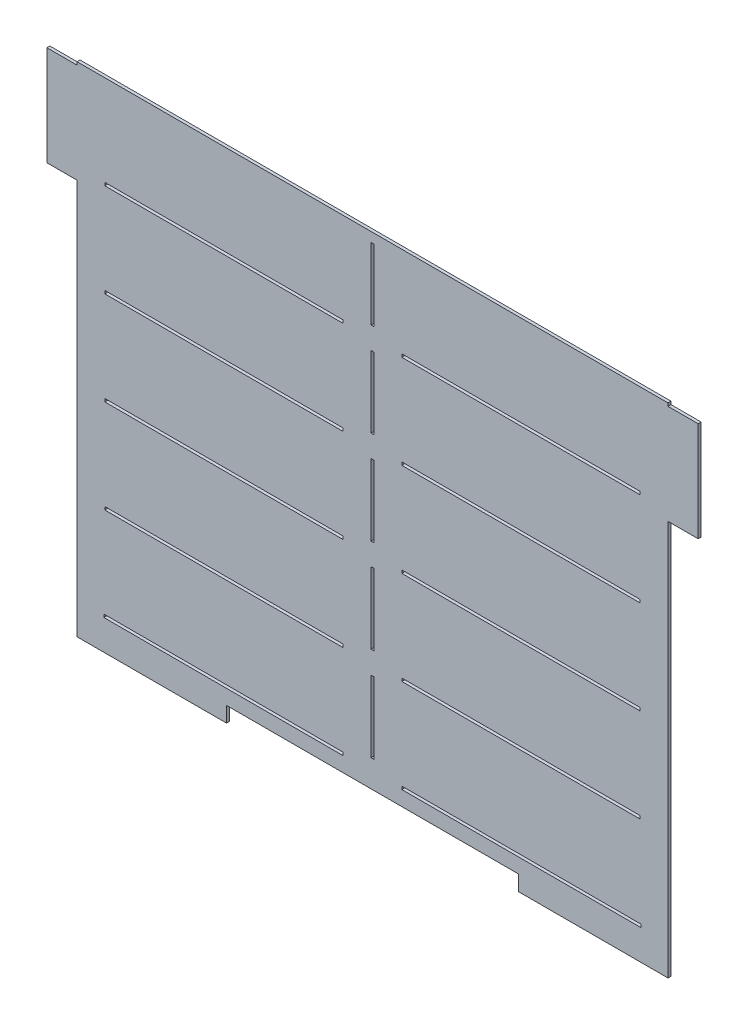
SolidWorks part; units mm, degrees
material "6061-T6 (SS)"
ref_plane "X-Y Datum" through (0, 0, 0) normal (0, 0, 1) x (1, 0, 0)
ref_plane "X-Z Datum" through (0, 0, 0) normal (0, 1, 0) x (1, 0, 0)
ref_plane "Y-Z Datum" through (0, 0, 0) normal (1, 0, 0) x (0, 0, -1)
sketch "Sketch1" plane through (0, 0, 0) normal (0, 0, 1) x (1, 0, 0)
  line L0 (-1.27, -1.27) -> (-1.27, 95.3084)
  line L1 (0, 0) -> (310.8274, 0)
  line L2 (0, 0) -> (0, 94.0384)
  line L3 (0, 94.0384) -> (310.8274, 94.0384)
  line L4 (310.8274, 0) -> (310.8274, 94.0384)
  line L5 (-1.27, 95.3084) -> (312.0974, 95.3084)
  line L6 (312.0974, -1.27) -> (312.0974, 95.3084)
  line L7 (-1.27, -1.27) -> (312.0974, -1.27)
  line L8 (-2.8575, 96.8959) -> (313.6849, 96.8959)
  line L9 (313.6849, -2.8575) -> (313.6849, 96.8959)
  line L10 (-2.8575, -2.8575) -> (313.6849, -2.8575)
  line L11 (-2.8575, -2.8575) -> (-2.8575, 96.8959)
  line L12 (0, 99.7534) -> (310.8274, 99.7534)
  line L13 (310.8274, 193.7918) -> (310.8274, 99.7534)
  line L14 (0, 193.7918) -> (310.8274, 193.7918)
  line L15 (0, 193.7918) -> (0, 99.7534)
  line L16 (-1.27, 195.0618) -> (312.0974, 195.0618)
  line L17 (312.0974, 195.0618) -> (312.0974, 98.4834)
  line L18 (-1.27, 98.4834) -> (312.0974, 98.4834)
  line L19 (-1.27, 195.0618) -> (-1.27, 98.4834)
  line L20 (-2.8575, 196.6493) -> (-2.8575, 96.8959)
  line L21 (-2.8575, 196.6493) -> (630.2273, 196.6493)
  line L23 (-2.8575, 296.4028) -> (630.2273, 296.4028)
  line L24 (-1.27, 198.2368) -> (-1.27, 294.8153)
  line L25 (-1.27, 294.8153) -> (312.0974, 294.8153)
  line L26 (312.0974, 198.2368) -> (312.0974, 294.8153)
  line L27 (-1.27, 198.2368) -> (312.0974, 198.2368)
  line L28 (0, 199.5068) -> (0, 293.5453)
  line L29 (0, 199.5068) -> (310.8274, 199.5068)
  line L30 (310.8274, 199.5068) -> (310.8274, 293.5453)
  line L31 (0, 293.5453) -> (310.8274, 293.5453)
  line L33 (313.6849, 96.8959) -> (313.6849, 196.6493)
  line L34 (-2.8575, 396.1562) -> (630.2273, 396.1562)
  line L35 (-1.27, 394.5687) -> (312.0974, 394.5687)
  line L36 (312.0974, 394.5687) -> (312.0974, 297.9903)
  line L37 (-1.27, 297.9903) -> (312.0974, 297.9903)
  line L38 (-1.27, 394.5687) -> (-1.27, 297.9903)
  line L39 (0, 393.2987) -> (310.8274, 393.2987)
  line L40 (310.8274, 393.2987) -> (310.8274, 299.2603)
  line L41 (0, 299.2603) -> (310.8274, 299.2603)
  line L42 (0, 393.2987) -> (0, 299.2603)
  line L43 (-2.8575, 296.4028) -> (-2.8575, 196.6493)
  line L44 (-2.8575, 495.9096) -> (-2.8575, 296.4028)
  line L45 (313.6849, 495.9096) -> (313.6849, 296.4028)
  line L46 (313.6849, 196.6493) -> (313.6849, 296.4028)
  line L47 (-2.8575, 495.9096) -> (630.2273, 495.9096)
  line L48 (-1.27, 397.7437) -> (-1.27, 494.3221)
  line L49 (-1.27, 494.3221) -> (312.0974, 494.3221)
  line L50 (312.0974, 397.7437) -> (312.0974, 494.3221)
  line L51 (-1.27, 397.7437) -> (312.0974, 397.7437)
  line L52 (0, 399.0137) -> (0, 493.0521)
  line L53 (0, 493.0521) -> (310.8274, 493.0521)
  line L54 (310.8274, 399.0137) -> (310.8274, 493.0521)
  line L55 (0, 399.0137) -> (310.8274, 399.0137)
  line L56 (313.6849, 595.663) -> (313.6849, 495.9096) construction
  line L57 (628.6398, 397.7437) -> (315.2724, 397.7437)
  line L58 (315.2724, 397.7437) -> (315.2724, 494.3221)
  line L59 (628.6398, 494.3221) -> (315.2724, 494.3221)
  line L60 (628.6398, 397.7437) -> (628.6398, 494.3221)
  line L61 (627.3698, 399.0137) -> (316.5424, 399.0137)
  line L62 (316.5424, 399.0137) -> (316.5424, 493.0521)
  line L63 (627.3698, 493.0521) -> (316.5424, 493.0521)
  line L64 (627.3698, 399.0137) -> (627.3698, 493.0521)
  line L65 (630.2273, 495.9096) -> (630.2273, 296.4028)
  line L66 (628.6398, 394.5687) -> (628.6398, 297.9903)
  line L67 (628.6398, 297.9903) -> (315.2724, 297.9903)
  line L68 (315.2724, 394.5687) -> (315.2724, 297.9903)
  line L69 (628.6398, 394.5687) -> (315.2724, 394.5687)
  line L70 (627.3698, 393.2987) -> (627.3698, 299.2603)
  line L71 (627.3698, 299.2603) -> (316.5424, 299.2603)
  line L72 (316.5424, 393.2987) -> (316.5424, 299.2603)
  line L73 (627.3698, 393.2987) -> (316.5424, 393.2987)
  line L74 (630.2273, 296.4028) -> (630.2273, 196.6493)
  line L75 (628.6398, 198.2368) -> (315.2724, 198.2368)
  line L76 (315.2724, 198.2368) -> (315.2724, 294.8153)
  line L77 (628.6398, 294.8153) -> (315.2724, 294.8153)
  line L78 (628.6398, 198.2368) -> (628.6398, 294.8153)
  line L79 (627.3698, 199.5068) -> (316.5424, 199.5068)
  line L80 (316.5424, 199.5068) -> (316.5424, 293.5453)
  line L81 (627.3698, 293.5453) -> (316.5424, 293.5453)
  line L82 (627.3698, 199.5068) -> (627.3698, 293.5453)
  line L83 (630.2273, 196.6493) -> (630.2273, 96.8959)
  line L84 (628.6398, 195.0618) -> (628.6398, 98.4834)
  line L85 (628.6398, 98.4834) -> (315.2724, 98.4834)
  line L86 (315.2724, 195.0618) -> (315.2724, 98.4834)
  line L87 (628.6398, 195.0618) -> (315.2724, 195.0618)
  line L88 (627.3698, 193.7918) -> (627.3698, 99.7534)
  line L89 (627.3698, 193.7918) -> (316.5424, 193.7918)
  line L90 (316.5424, 193.7918) -> (316.5424, 99.7534)
  line L91 (627.3698, 99.7534) -> (316.5424, 99.7534)
  line L92 (630.2273, -2.8575) -> (630.2273, 96.8959)
  line L93 (630.2273, -2.8575) -> (313.6849, -2.8575)
  line L94 (313.6849, -2.8575) -> (313.6849, 96.8959)
  line L95 (630.2273, 96.8959) -> (313.6849, 96.8959)
  line L96 (628.6398, -1.27) -> (315.2724, -1.27)
  line L97 (315.2724, -1.27) -> (315.2724, 95.3084)
  line L98 (628.6398, 95.3084) -> (315.2724, 95.3084)
  line L99 (628.6398, -1.27) -> (628.6398, 95.3084)
  line L100 (627.3698, 94.0384) -> (316.5424, 94.0384)
  line L101 (316.5424, 0) -> (316.5424, 94.0384)
  line L102 (627.3698, 0) -> (316.5424, 0)
  line L103 (627.3698, 0) -> (627.3698, 94.0384)
  point P56 (313.6849, 396.1562)
  dimension "D1" = 310.8274
  dimension "D2" = 94.0384
  dimension "D3" = 1.27
  dimension "D4" = 1.5875
sketch "Sketch2" plane through (0, 0, 0) normal (0, 0, 1) x (1, 0, 0)
  line L0 (0, 47.0192) -> (310.8274, 47.0192) construction
  line L1 (-1.27, -1.27) -> (628.6398, -1.27)
  line L2 (-1.27, -1.27) -> (-1.27, 494.3221)
  line L3 (-1.27, 494.3221) -> (628.6398, 494.3221)
  line L4 (628.6398, -1.27) -> (628.6398, 494.3221)
  line L5 (0, 0) -> (0, 94.0384) construction
  line L6 (310.8274, 0) -> (310.8274, 94.0384) construction
  line L7 (155.4137, 47.0192) -> (155.4137, 163.8162) construction
  line L8 (-2.8575, 96.8959) -> (313.6849, 96.8959) construction
  line L9 (28.4137, 95.3084) -> (282.4137, 95.3084)
  line L10 (28.4137, 95.3084) -> (28.4137, 98.4834)
  line L11 (28.4137, 98.4834) -> (282.4137, 98.4834)
  line L12 (282.4137, 95.3084) -> (282.4137, 98.4834)
  line L13 (28.4137, 95.3084) -> (282.4137, 98.4834) construction
  line L14 (28.4137, 98.4834) -> (282.4137, 95.3084) construction
  line L15 (-1.27, 98.4834) -> (312.0974, 98.4834) construction
  line L16 (-2.8575, 196.6493) -> (630.2273, 196.6493) construction
  line L17 (28.4137, 195.0618) -> (282.4137, 195.0618)
  line L18 (28.4137, 195.0618) -> (28.4137, 198.2368)
  line L19 (28.4137, 198.2368) -> (282.4137, 198.2368)
  line L20 (282.4137, 195.0618) -> (282.4137, 198.2368)
  line L21 (28.4137, 195.0618) -> (282.4137, 198.2368) construction
  line L22 (28.4137, 198.2368) -> (282.4137, 195.0618) construction
  line L23 (-1.27, 198.2368) -> (312.0974, 198.2368) construction
  line L24 (315.2724, -1.27) -> (315.2724, 95.3084) construction
  line L25 (-2.8575, 296.4028) -> (630.2273, 296.4028) construction
  line L26 (28.4137, 294.8153) -> (282.4137, 294.8153)
  line L27 (28.4137, 294.8153) -> (28.4137, 297.9903)
  line L28 (28.4137, 297.9903) -> (282.4137, 297.9903)
  line L29 (282.4137, 294.8153) -> (282.4137, 297.9903)
  line L30 (28.4137, 294.8153) -> (282.4137, 297.9903) construction
  line L31 (28.4137, 297.9903) -> (282.4137, 294.8153) construction
  line L32 (-1.27, 297.9903) -> (312.0974, 297.9903) construction
  line L33 (-2.8575, 396.1562) -> (630.2273, 396.1562) construction
  line L34 (28.4137, 394.5687) -> (282.4137, 394.5687)
  line L35 (28.4137, 394.5687) -> (28.4137, 397.7437)
  line L36 (28.4137, 397.7437) -> (282.4137, 397.7437)
  line L37 (282.4137, 394.5687) -> (282.4137, 397.7437)
  line L38 (28.4137, 394.5687) -> (282.4137, 397.7437) construction
  line L39 (28.4137, 397.7437) -> (282.4137, 394.5687) construction
  line L40 (-1.27, 397.7437) -> (312.0974, 397.7437) construction
  line L41 (313.6849, 604.3732) -> (313.6849, -52.4712) construction
  line L42 (598.9561, 98.4834) -> (344.9561, 98.4834)
  line L43 (344.9561, 95.3084) -> (344.9561, 98.4834)
  line L44 (598.9561, 95.3084) -> (344.9561, 95.3084)
  line L45 (598.9561, 95.3084) -> (598.9561, 98.4834)
  line L46 (598.9561, 198.2368) -> (344.9561, 198.2368)
  line L47 (344.9561, 195.0618) -> (344.9561, 198.2368)
  line L48 (598.9561, 195.0618) -> (344.9561, 195.0618)
  line L49 (598.9561, 195.0618) -> (598.9561, 198.2368)
  line L50 (598.9561, 397.7437) -> (344.9561, 397.7437)
  line L51 (344.9561, 394.5687) -> (344.9561, 397.7437)
  line L52 (598.9561, 394.5687) -> (344.9561, 394.5687)
  line L53 (598.9561, 394.5687) -> (598.9561, 397.7437)
  line L54 (598.9561, 297.9903) -> (344.9561, 297.9903)
  line L55 (344.9561, 294.8153) -> (344.9561, 297.9903)
  line L56 (598.9561, 294.8153) -> (344.9561, 294.8153)
  line L57 (598.9561, 294.8153) -> (598.9561, 297.9903)
  line L58 (312.0974, 8.5255) -> (315.2724, 8.5255)
  line L59 (312.0974, 8.5255) -> (312.0974, 84.7255)
  line L60 (312.0974, 84.7255) -> (315.2724, 84.7255)
  line L61 (315.2724, 8.5255) -> (315.2724, 84.7255)
  line L62 (312.0974, 8.5255) -> (315.2724, 84.7255) construction
  line L63 (312.0974, 84.7255) -> (315.2724, 8.5255) construction
  line L64 (310.8274, 193.7918) -> (310.8274, 99.7534) construction
  line L65 (310.8274, 146.7726) -> (337.6409, 146.7726) construction
  line L66 (315.2724, 195.0618) -> (315.2724, 98.4834) construction
  line L67 (312.0974, 108.6726) -> (315.2724, 108.6726)
  line L68 (312.0974, 108.6726) -> (312.0974, 184.8726)
  line L69 (312.0974, 184.8726) -> (315.2724, 184.8726)
  line L70 (315.2724, 108.6726) -> (315.2724, 184.8726)
  line L71 (312.0974, 108.6726) -> (315.2724, 184.8726) construction
  line L72 (312.0974, 184.8726) -> (315.2724, 108.6726) construction
  line L73 (310.8274, 293.5453) -> (310.8274, 199.5068) construction
  line L74 (310.8274, 246.5261) -> (343.3258, 246.5261) construction
  line L75 (315.2724, 198.2368) -> (315.2724, 294.8153) construction
  line L76 (312.0974, 208.4261) -> (315.2724, 208.4261)
  line L77 (312.0974, 208.4261) -> (312.0974, 284.6261)
  line L78 (312.0974, 284.6261) -> (315.2724, 284.6261)
  line L79 (315.2724, 208.4261) -> (315.2724, 284.6261)
  line L80 (312.0974, 208.4261) -> (315.2724, 284.6261) construction
  line L81 (312.0974, 284.6261) -> (315.2724, 208.4261) construction
  line L82 (310.8274, 299.2603) -> (310.8274, 393.2987) construction
  line L83 (310.8274, 493.0521) -> (310.8274, 399.0137) construction
  line L84 (310.8274, 346.2795) -> (351.536, 346.2795) construction
  line L85 (310.8274, 446.0329) -> (345.4409, 446.0329) construction
  line L86 (315.2724, 394.5687) -> (315.2724, 297.9903) construction
  line L87 (312.0974, 308.1795) -> (315.2724, 308.1795)
  line L88 (312.0974, 308.1795) -> (312.0974, 384.3795)
  line L89 (312.0974, 384.3795) -> (315.2724, 384.3795)
  line L90 (315.2724, 308.1795) -> (315.2724, 384.3795)
  line L91 (312.0974, 308.1795) -> (315.2724, 384.3795) construction
  line L92 (312.0974, 384.3795) -> (315.2724, 308.1795) construction
  line L93 (315.2724, 397.7437) -> (315.2724, 494.3221) construction
  line L94 (312.0974, 407.9329) -> (315.2724, 407.9329)
  line L95 (312.0974, 407.9329) -> (312.0974, 484.1329)
  line L96 (312.0974, 484.1329) -> (315.2724, 484.1329)
  line L97 (315.2724, 407.9329) -> (315.2724, 484.1329)
  line L98 (312.0974, 407.9329) -> (315.2724, 484.1329) construction
  line L99 (312.0974, 484.1329) -> (315.2724, 407.9329) construction
  point P13 (155.4137, 96.8959)
  point P23 (155.4137, 196.6493)
  point P32 (155.4137, 296.4028)
  point P41 (155.4137, 396.1562)
  point P52 (313.6849, 46.6255)
  point P80 (313.6849, 146.7726)
  point P93 (313.6849, 246.526)
  point P114 (313.6849, 346.2795)
  point P122 (313.6849, 446.0329)
  dimension "D1" = 254
  dimension "D2" = 254
  dimension "D3" = 254
  dimension "D4" = 254
  dimension "D5" = 76.2
  dimension "D6" = 76.2
  dimension "D7" = 3.175
  dimension "D8" = 99.7534
  dimension "D9" = 76.2
  dimension "D10" = 99.7534
  dimension "D11" = 99.7534
  dimension "D12" = 99.7534
  dimension "D13" = 76.2
  dimension "D14" = 76.2
extrude "Boss-Extrude1" add sketch "Sketch2" along normal blind 3.175
sketch "Sketch4" plane through (0, 0, 3.175) normal (0, 0, 1) x (1, 0, 0)
  line L0 (313.6849, 484.1329) -> (313.6849, 506.6663) construction
  line L1 (-1.27, -1.27) -> (27.315, -1.27)
  line L2 (-1.27, -1.27) -> (-1.27, -4.445)
  line L3 (-1.27, -4.445) -> (27.315, -4.445)
  line L4 (628.6398, -1.27) -> (628.6398, -4.445)
  line L6 (27.315, -1.27) -> (27.315, -4.445)
  line L8 (282.4137, -1.27) -> (282.4137, -4.445)
  line L9 (600.0548, -1.27) -> (628.6398, -1.27)
  line L11 (344.9561, -1.27) -> (344.9561, -4.445)
  line L13 (600.0548, -1.27) -> (600.0548, -4.445)
  line L14 (600.0548, -4.445) -> (628.6398, -4.445)
  line L15 (282.4137, -1.27) -> (344.9561, -1.27)
  line L16 (282.4137, -4.445) -> (344.9561, -4.445)
extrude "Boss-Extrude2" add sketch "Sketch4" against normal through all
sketch "Sketch5" plane through (0, 0, 3.175) normal (0, 0, 1) x (1, 0, 0)
  line L0 (313.6849, 646.2482) -> (313.6849, -137.2183) construction
  line L9 (628.6398, 526.4531) -> (469.3361, 526.4531) construction
  line L18 (469.3361, 510.1236) -> (469.3361, 526.4531) construction
  line L19 (-1.27, 494.3221) -> (628.6398, 494.3221) construction
  line L20 (-1.27, 494.3221) -> (-1.27, 497.4971) construction
  line L21 (158.0337, 510.1236) -> (469.3361, 510.1236) construction
  line L22 (628.6398, 494.3221) -> (628.6398, 497.4971) construction
  line L24 (-1.27, 497.4971) -> (-1.27, 526.4531) construction
  line L25 (-1.27, 526.4531) -> (158.0337, 526.4531) construction
  line L26 (158.0337, 510.1236) -> (158.0337, 526.4531) construction
  line L28 (628.6398, 497.4971) -> (628.6398, 526.4531) construction
  line L29 (-1.27, 244.9386) -> (684.2814, 244.9386) construction
  line L31 (158.0337, -20.2465) -> (158.0337, -36.576)
  line L32 (-1.27, -36.576) -> (158.0337, -36.576)
  line L33 (-1.27, -7.62) -> (-1.27, -36.576)
  line L34 (-1.27, -4.445) -> (-1.27, -7.62)
  line L35 (-1.27, -4.445) -> (628.6398, -4.445)
  line L36 (628.6398, -4.445) -> (628.6398, -7.62)
  line L37 (628.6398, -7.62) -> (628.6398, -36.576)
  line L38 (628.6398, -36.576) -> (469.3361, -36.576)
  line L39 (469.3361, -20.2465) -> (469.3361, -36.576)
  line L40 (158.0337, -20.2465) -> (469.3361, -20.2465)
  line L41 (628.6398, 491.1471) -> (628.6398, 384.9446)
  line L42 (628.6398, 491.1471) -> (660.7708, 491.1471)
  line L43 (660.7708, 491.1471) -> (660.7708, 384.9446)
  line L44 (628.6398, 384.9446) -> (660.7708, 384.9446)
  line L45 (-1.27, 384.9446) -> (-33.401, 384.9446)
  line L46 (-33.401, 491.1471) -> (-33.401, 384.9446)
  line L47 (-1.27, 491.1471) -> (-33.401, 491.1471)
  line L48 (-1.27, 491.1471) -> (-1.27, 384.9446)
  dimension "D1" = 3.175
extrude "Boss-Extrude3" add sketch "Sketch5" against normal through all
